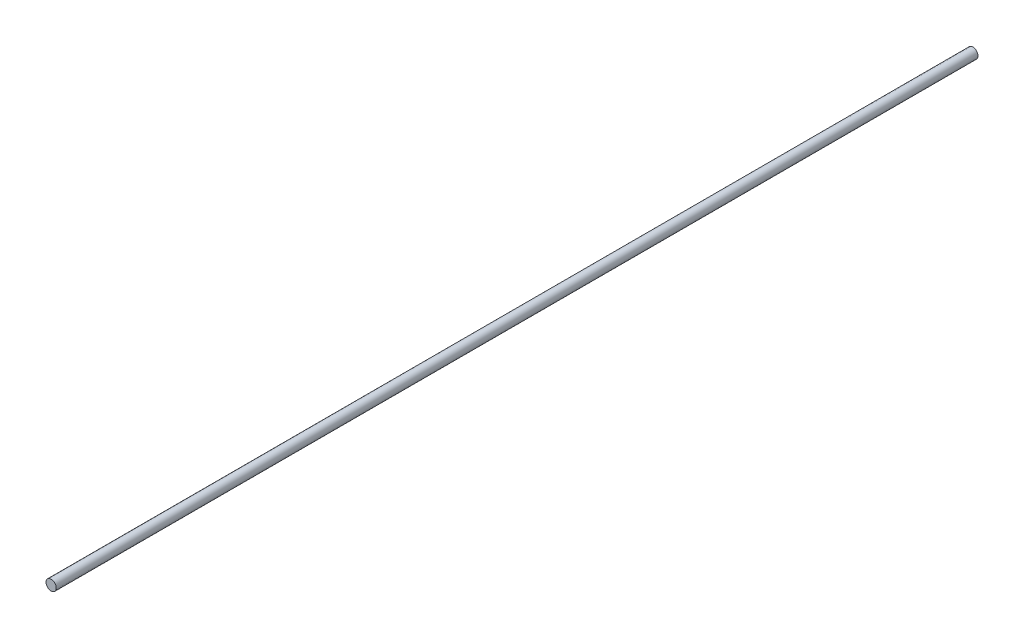
SolidWorks part; units mm, degrees
material "Hexcel AS4C (3000 Filaments)"
ref_plane "Front Plane" through (0, 0, 0) normal (0, 0, 1) x (1, 0, 0)
ref_plane "Top Plane" through (0, 0, 0) normal (0, 1, 0) x (1, 0, 0)
ref_plane "Right Plane" through (0, 0, 0) normal (1, 0, 0) x (0, 0, -1)
sketch "Sketch1" plane through (0, 0, 0) normal (0, 0, 1) x (1, 0, 0)
  circle A0 centre (0, 0) radius 1
  dimension "D1" = 2
extrude "Boss-Extrude1" add sketch "Sketch1" along normal blind 180
